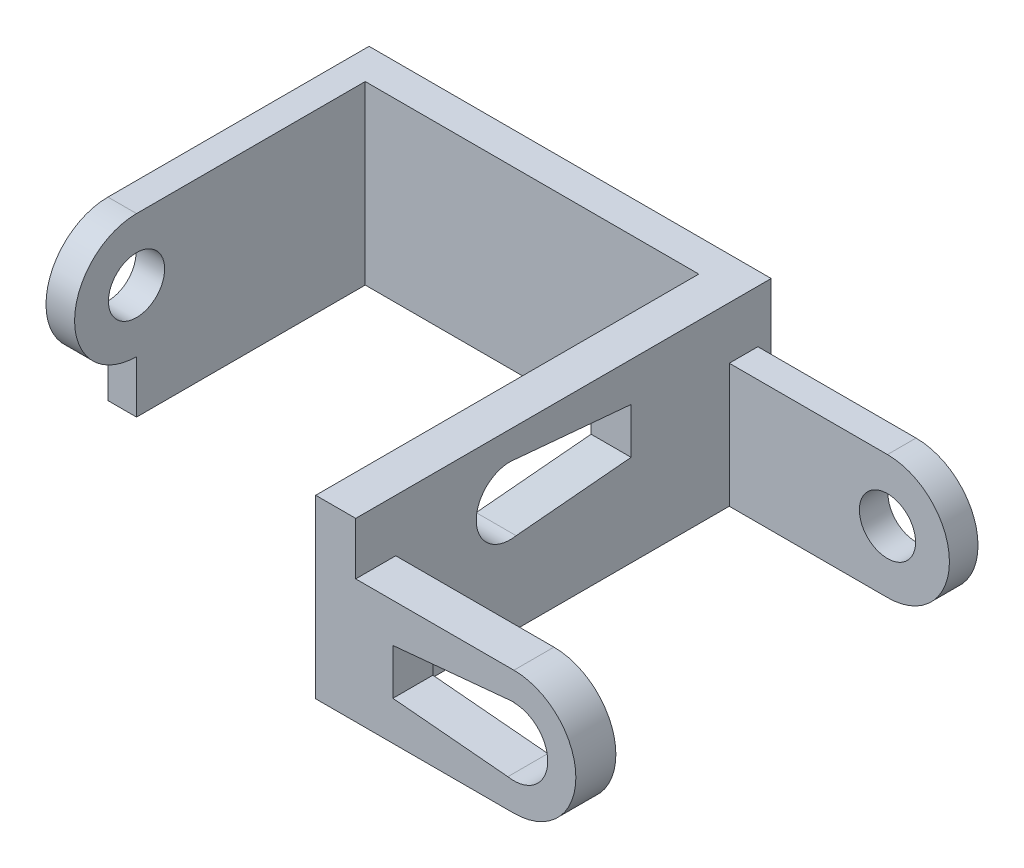
SolidWorks part; units mm, degrees
material "ABS"
ref_plane "Front Plane" through (0, 0, 0) normal (0, 0, 1) x (1, 0, 0)
ref_plane "Top Plane" through (0, 0, 0) normal (0, 1, 0) x (1, 0, 0)
ref_plane "Right Plane" through (0, 0, 0) normal (1, 0, 0) x (0, 0, -1)
sketch "Sketch1" plane through (0, 0, 0) normal (1, 0, 0) x (0, 0, -1)
  line L1 (-16.2, 12) -> (27.4, 12)
  line L2 (-16.2, 12) -> (-16.2, 30.5)
  line L3 (-16.2, 30.5) -> (27.4, 30.5)
  line L4 (27.4, 12) -> (27.4, 30.5)
extrude "Boss-Extrude1" add sketch "Sketch1" along normal mid plane 4.2 from offset 34.9
sketch "Sketch2" plane through (0, 0, 0) normal (1, 0, 0) x (0, 0, -1)
  circle A0 centre (0, 24) radius 3.55
extrude "Cut-Extrude1" cut sketch "Sketch2" against normal mid plane 4.2 from offset 34.9
sketch "Sketch3" plane through (0, 0, 0) normal (1, 0, 0) x (0, 0, -1)
  line L0 (0, 20.45) -> (12.7, 21.5967)
  line L1 (12.7, 21.5967) -> (12.7, 26.4033)
  line L2 (12.7, 26.4033) -> (0, 27.55)
  line L3 (0, 27.55) -> (0, 20.45)
  circle A0 centre (0, 24) radius 3.55 construction
extrude "Cut-Extrude2" cut sketch "Sketch3" against normal mid plane 4.2 from offset 34.9
sketch "Sketch4" plane through (0, 0, 0) normal (0, 0, 1) x (1, 0, 0)
  circle A0 centre (-16.2, 18.5) radius 6.5
extrude "Boss-Extrude2" add sketch "Sketch4" along normal mid plane 4.2 from offset 14.1
sketch "Sketch5" plane through (0, 0, 0) normal (0, 0, 1) x (1, 0, 0)
  line L1 (-37, 12) -> (-16.2, 12)
  line L2 (-37, 12) -> (-37, 25)
  line L3 (-37, 25) -> (-16.2, 25)
  line L4 (-16.2, 12) -> (-16.2, 25)
  circle A0 centre (-16.2, 18.5) radius 6.5 construction
extrude "Boss-Extrude3" add sketch "Sketch5" along normal mid plane 4.2 from offset 14.1
sketch "Sketch6" plane through (0, 0, 0) normal (0, 0, 1) x (1, 0, 0)
  circle A0 centre (-16.2, 18.5) radius 3.55
extrude "Cut-Extrude3" cut sketch "Sketch6" against normal mid plane 4.2 from offset 14.1
sketch "Sketch7" plane through (0, 0, 0) normal (0, 0, 1) x (1, 0, 0)
  line L0 (-16.2, 22.1038) -> (-28.9, 20.9033)
  line L1 (-28.9, 20.9033) -> (-28.9, 16.0967)
  line L2 (-28.9, 16.0967) -> (-16.2, 14.95)
  line L3 (-16.2, 14.95) -> (-16.2, 22.1038)
  circle A0 centre (-16.2, 18.5) radius 3.55 construction
extrude "Cut-Extrude4" cut sketch "Sketch7" against normal mid plane 4.2 from offset 14.1
sketch "Sketch8" plane through (0, 0, 0) normal (0, 0, 1) x (1, 0, 0)
  circle A0 centre (-16.2, 18.5) radius 6.5
extrude "Boss-Extrude4" add sketch "Sketch8" along normal mid plane 3 from offset 24.5
sketch "Sketch9" plane through (0, 0, 0) normal (0, 0, 1) x (1, 0, 0)
  line L1 (-37, 12) -> (-16.2, 12)
  line L2 (-37, 12) -> (-37, 25)
  line L3 (-37, 25) -> (-16.2, 25)
  line L4 (-16.2, 12) -> (-16.2, 25)
extrude "Boss-Extrude5" add sketch "Sketch9" along normal mid plane 3 from offset 24.5
sketch "Sketch10" plane through (0, 0, 0) normal (0, 0, 1) x (1, 0, 0)
  circle A0 centre (-16.2, 18.5) radius 2.95
extrude "Cut-Extrude5" cut sketch "Sketch10" against normal mid plane 3 from offset 24.5
sketch "Sketch11" plane through (0, 0, 0) normal (0, 0, 1) x (1, 0, 0)
  line L1 (-75, 12) -> (-32.8, 12)
  line L2 (-75, 12) -> (-75, 30.5)
  line L3 (-75, 30.5) -> (-32.8, 30.5)
  line L4 (-32.8, 12) -> (-32.8, 30.5)
extrude "Boss-Extrude6" add sketch "Sketch11" along normal mid plane 3.4 from offset 25.7
sketch "Sketch12" plane through (0, 0, 0) normal (1, 0, 0) x (0, 0, -1)
  circle A0 centre (0, 24) radius 6.5
extrude "Boss-Extrude7" add sketch "Sketch12" along normal mid plane 3 from offset 73.5
sketch "Sketch13" plane through (0, 0, 0) normal (1, 0, 0) x (0, 0, -1)
  line L0 (-12, 12) -> (23, 12) construction
  line L1 (0, 12) -> (27.4, 12)
  line L2 (0, 12) -> (0, 30.5)
  line L3 (0, 30.5) -> (27.4, 30.5)
  line L4 (27.4, 12) -> (27.4, 30.5)
extrude "Boss-Extrude8" add sketch "Sketch13" along normal mid plane 3 from offset 73.5
sketch "Sketch14" plane through (0, 0, 0) normal (1, 0, 0) x (0, 0, -1)
  circle A0 centre (0, 24) radius 2.95
extrude "Cut-Extrude6" cut sketch "Sketch14" against normal mid plane 3 from offset 73.5
